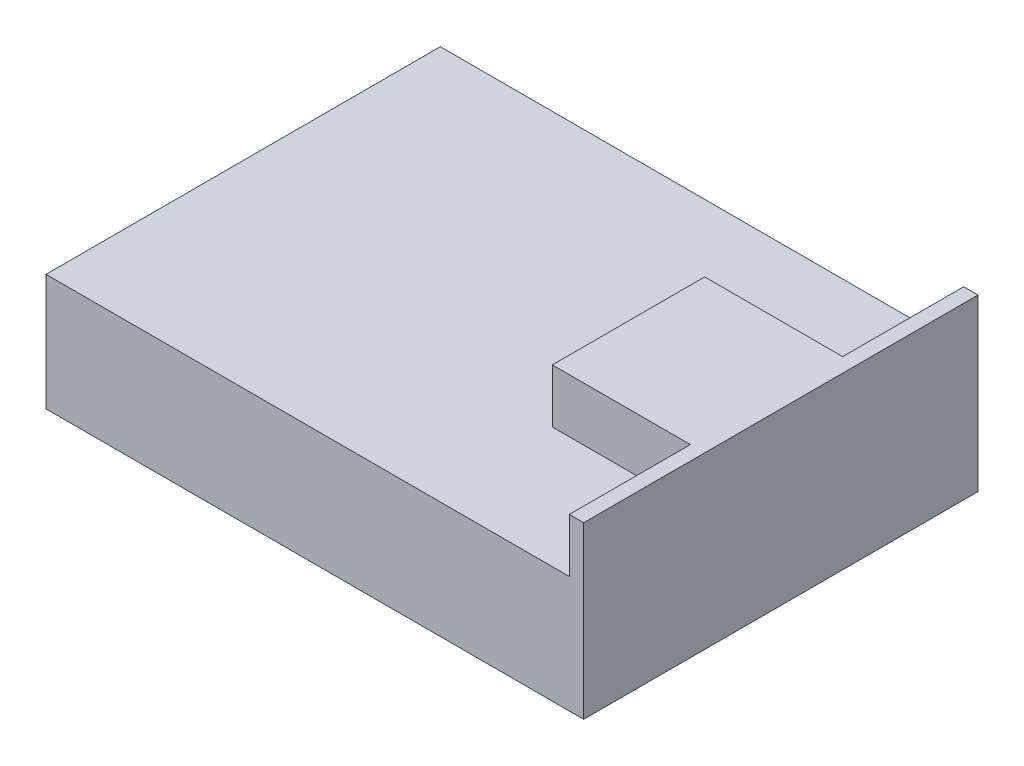
SolidWorks part; units mm, degrees
ref_plane "前视基准面" through (0, 0, 0) normal (0, 0, 1) x (1, 0, 0)
ref_plane "上视基准面" through (0, 0, 0) normal (0, 1, 0) x (1, 0, 0)
ref_plane "右视基准面" through (0, 0, 0) normal (1, 0, 0) x (0, 0, -1)
other "Configuration Table"
ref_plane "基准面1" through (0, 19, 0) normal (0, 1, 0) x (1, 0, 0)
sketch "草图1" plane through (0, 19, 0) normal (0, 1, 0) x (1, 0, 0)
  line L0 (30, 22) -> (-30, 22)
  line L1 (-30, 22) -> (-30, -22)
  line L2 (-30, -22) -> (30, -22)
  line L3 (30, -22) -> (30, 22)
  dimension "D1" = 60
  dimension "D2" = 44
extrude "凸台-拉伸1" add sketch "草图1" against normal blind 19
sketch "草图2" plane through (0, 0, -22) normal (0, 0, -1) x (-1, 0, 0)
  line L0 (-28.4, 19) -> (-28.4, 13)
  line L1 (-28.4, 13) -> (30, 13)
  line L2 (30, 13) -> (30, 19)
  line L3 (30, 19) -> (-28.4, 19)
  line L4 (-30, 0) -> (-30, 19) construction
  line L5 (-30, 19) -> (30, 19) construction
  dimension "D1" = 1.6
  dimension "D2" = 60
  dimension "D3" = 6
extrude "切除-拉伸1" cut sketch "草图2" against normal through all
sketch "草图3" plane through (0, 13, 0) normal (0, 1, 0) x (-1, 0, 0)
  line L0 (-13, -8.5) -> (-28.4, -8.5)
  line L1 (-28.4, -8.5) -> (-28.4, 8.5)
  line L2 (-28.4, 8.5) -> (-13, 8.5)
  line L3 (-13, 8.5) -> (-13, -8.5)
  line L4 (30, 22) -> (30, -22) construction
  line L5 (-28.4, -22) -> (30, -22) construction
  dimension "D1" = 43
  dimension "D2" = 58.4
  dimension "D3" = 13.5
  dimension "D4" = 30.5
extrude "凸台-拉伸2" add sketch "草图3" along normal blind 6
